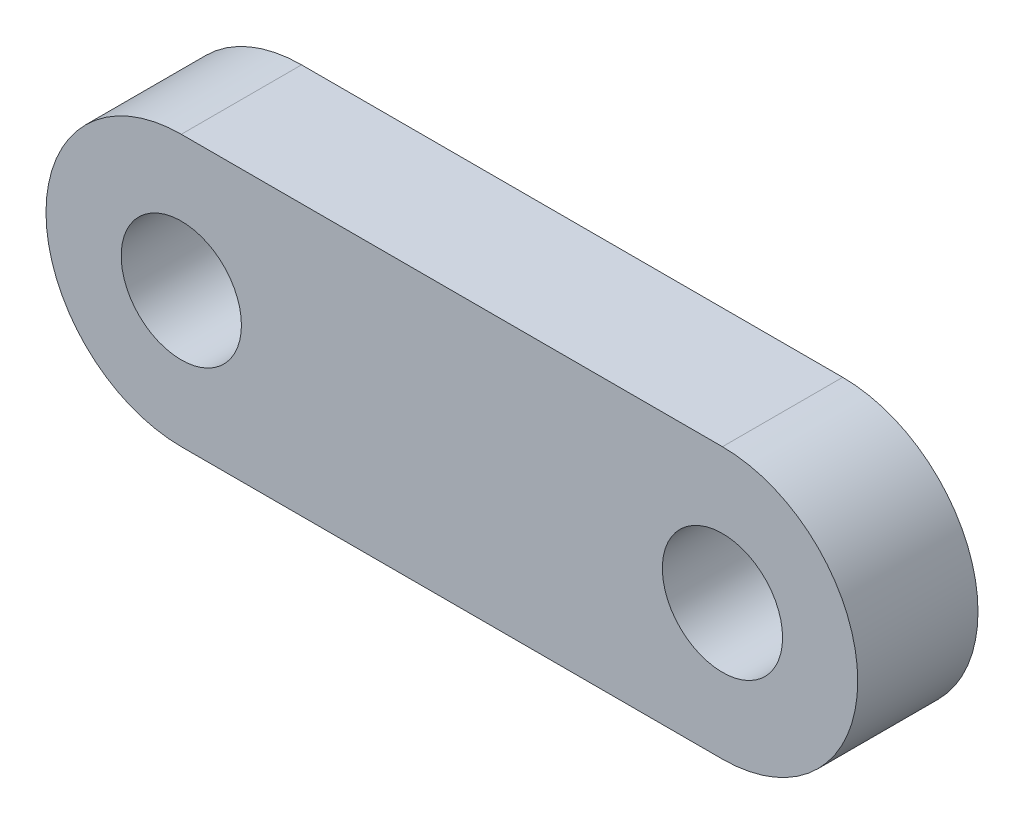
SolidWorks part; units mm, degrees
ref_plane "Спереди" through (0, 0, 0) normal (0, 0, 1) x (1, 0, 0)
ref_plane "Сверху" through (0, 0, 0) normal (0, 1, 0) x (1, 0, 0)
ref_plane "Справа" through (0, 0, 0) normal (1, 0, 0) x (0, 0, -1)
sketch "Эскиз1" plane through (0, 0, 0) normal (0, 0, 1) x (1, 0, 0)
  line L0 (0, 4.5) -> (18, 4.5)
  line L1 (0, -4.5) -> (18, -4.5)
  circle A0 centre (0, 0) radius 2
  circle A1 centre (18, 0) radius 2
  arc A2 (0, 4.5) -> (0, -4.5) centre (0, 0) ccw
  arc A3 (18, -4.5) -> (18, 4.5) centre (18, 0) ccw
  dimension "D1" = 18
extrude "Вытянуть1" add sketch "Эскиз1" along normal blind 4
